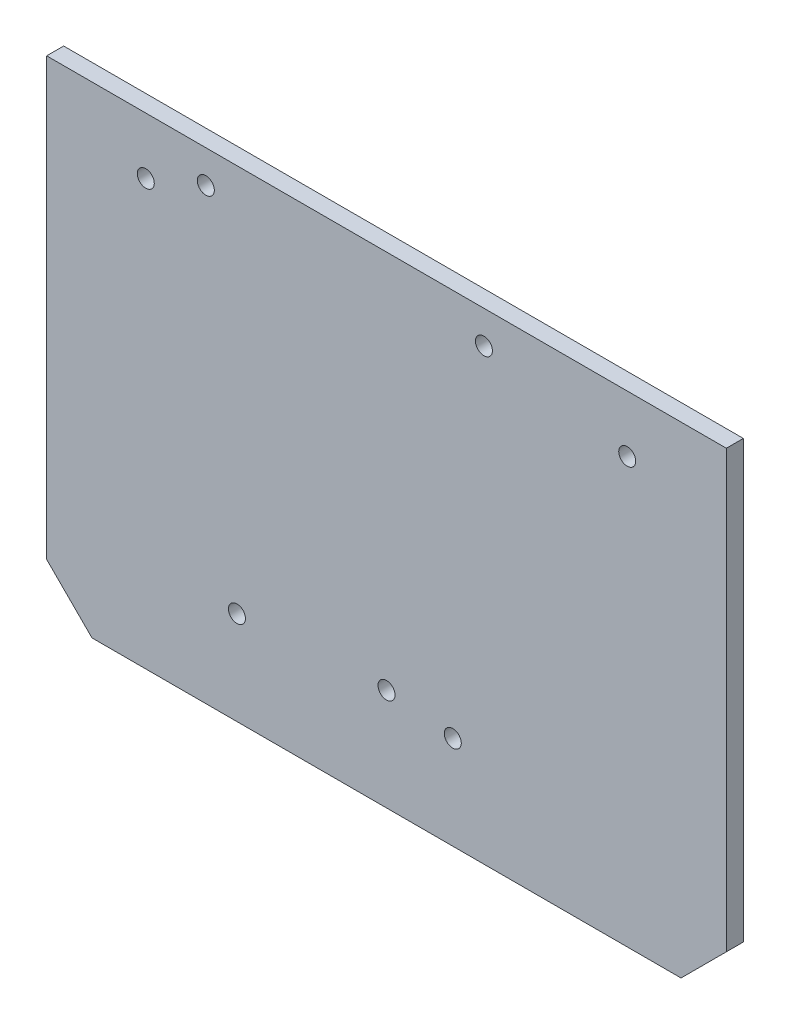
SolidWorks part; units mm, degrees
ref_plane "前视基准面" through (0, 0, 0) normal (0, 0, 1) x (1, 0, 0)
ref_plane "上视基准面" through (0, 0, 0) normal (0, 1, 0) x (1, 0, 0)
ref_plane "右视基准面" through (0, 0, 0) normal (1, 0, 0) x (0, 0, -1)
sketch "草图1" plane through (0, 0, 0) normal (0, 0, 1) x (1, 0, 0)
  line L1 (-60, 42.5) -> (60, 42.5)
  line L2 (-60, 42.5) -> (-60, -42.5)
  line L3 (-60, -42.5) -> (60, -42.5)
  line L4 (60, 42.5) -> (60, -42.5)
  line L5 (-60, 42.5) -> (60, -42.5) construction
  line L6 (-60, -42.5) -> (60, 42.5) construction
  point P0 (0, 0)
  dimension "D1" = 120
  dimension "D2" = 85
extrude "凸台-拉伸1" add sketch "草图1" along normal blind 3
sketch "草图2" plane through (0, 0, 3) normal (0, 0, 1) x (1, 0, 0)
  line L0 (0, 42.5) -> (0, -42.5) construction
  line L1 (60, 42.5) -> (-60, 42.5) construction
  line L2 (-60, -42.5) -> (60, -42.5) construction
  circle A0 centre (0, -24.5) radius 1.5
  circle A1 centre (-42.5, 32.5) radius 1.5
  circle A3 centre (42.5, 32.5) radius 1.5
  dimension "D1" = 18
  dimension "D2" = 85
  dimension "D3" = 75
  dimension "D4" = 3
  dimension "D5" = 3
extrude "切除-拉伸1" cut sketch "草图2" against normal through all
chamfer "倒角1" distance 8 angle 45 2 edges at (60, -42.5, 1.5) (-60, -42.5, 1.5)
sketch "草图3" plane through (0, 0, 3) normal (0, 0, 1) x (1, 0, 0)
  line L0 (-7.3505, 42.5) -> (-7.3505, -42.5) construction
  line L2 (-52, -42.5) -> (52, -42.5) construction
  circle A0 centre (-31.9005, 36.7375) radius 1.5
  circle A1 centre (-26.4005, -26) radius 1.5
  circle A2 centre (11.6995, -26) radius 1.5
  circle A3 centre (17.1995, 36.7375) radius 1.5
  point P14 (19.05, -29.3523)
  point P15 (19.05, -25.9784)
  dimension "D1" = 3
  dimension "D2" = 3
  dimension "D3" = 38.1
  dimension "D4" = 49.1
  dimension "D5" = 76.4
  dimension "D6" = 16.5
extrude "切除-拉伸2" cut sketch "草图3" against normal through all
